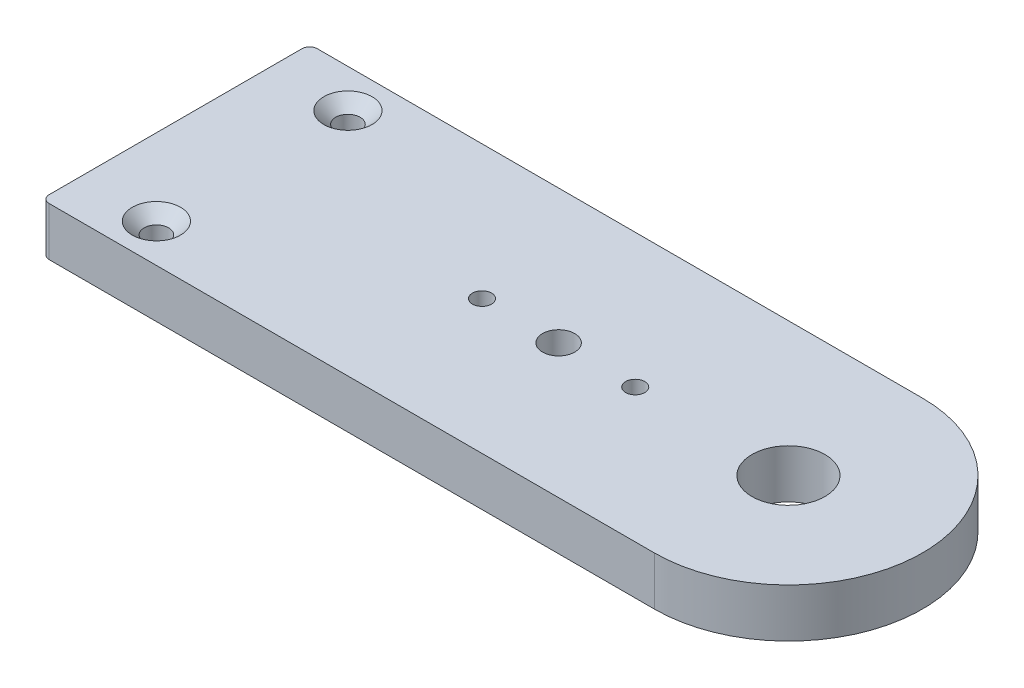
SolidWorks part; units mm, degrees
other "Markup1"
sketch "Sketch6" plane through (50.3553, 0, 50.3553) normal (0.291, 0.9567, 0.0091) x (0.9567, -0.291, -0.0015)
material "5052-H32"
ref_plane "Front Plane" through (0, 0, 0) normal (0, 0, 1) x (1, 0, 0)
ref_plane "Top Plane" through (0, 0, 0) normal (0, 1, 0) x (1, 0, 0)
ref_plane "Right Plane" through (0, 0, 0) normal (1, 0, 0) x (0, 0, -1)
sketch "Sketch2" plane through (0, 0, 0) normal (0, 1, 0) x (1, 0, 0)
  line L0 (0, 0) -> (70, 0) construction
  line L5 (0, 12.5) -> (0, -12.5) construction
  line L6 (-10, 17.5) -> (-10, -17.5)
  line L7 (-10, 17.5) -> (70, 17.5)
  line L8 (-10, -17.5) -> (70, -17.5)
  line L10 (25, 5) -> (55, 5) construction
  line L11 (25, 5) -> (25, -5) construction
  line L12 (25, -5) -> (55, -5) construction
  line L13 (55, 5) -> (55, -5) construction
  circle A0 centre (70, 0) radius 4.7625
  arc A2 (70, 17.5) -> (70, -17.5) centre (70, 0) cw
  circle A3 centre (0, 12.5) radius 1.5 construction
  circle A8 centre (70, 0) radius 37 construction
  circle A10 centre (0, -12.5) radius 1.5 construction
  circle A11 centre (30, 0) radius 1.5 construction
  circle A12 centre (50, 0) radius 1.5 construction
  circle A13 centre (40, 0) radius 2.5 construction
  point P0 (0, 0)
  point P21 (25, 0)
  point P27 (40, 5)
  point P28 (40, 0)
  dimension "D4" = 9.525
  dimension "D5" = 17.5
  dimension "D6" = 20
  dimension "D7" = 3
  dimension "D8" = 30
  dimension "D9" = 74
  dimension "D11" = 5
  dimension "D13" = 5
  dimension "D1" = 25
  dimension "D2" = 10
  dimension "D3" = 70
  dimension "D10" = 30
  dimension "D12" = 10
extrude "Boss-Extrude1" add sketch "Sketch2" against normal blind 6.35 contours L8 A2 L7
hole_wizard "CSK for M3 Flat Head Machine Screw1" positions "3DSketch1" profile "Sketch3" countersink size "M3" standard "ANSI Metric" end condition up to next
sketch3d "3DSketch1"
  point P0 (0, 0, -12.5)
  point P13 (0, 0, 12.5)
sketch "Sketch3" plane through (0, 0, -12.5) normal (1, 0, 0) x (0, 0, 1)
  line L0 (0, 0) -> (0, 6.35)
  line L1 (0, 6.35) -> (1.6, 6.35)
  line L2 (1.6, 6.35) -> (1.6, 1.55)
  line L3 (1.6, 1.55) -> (3.15, 0)
  line L5 (3.15, 0) -> (0, 0)
  line L6 (-1.6, 1.55) -> (-3.15, 0) construction
  line L11 (0, -6.35) -> (0, 107.95) construction
  dimension "Thru Hole Dia." = 3.2
  dimension "Thru Hole Depth" = 6.35
  dimension "Near C'Sink Dia." = 6.3
  dimension "Near C'Sink Angle" = 90
hole_wizard "Tap Drill for M3x0.5 Tap1" positions "3DSketch2" profile "Sketch7" hole size "M3x0.5" standard "ANSI Metric" end condition up to next
sketch3d "3DSketch2"
  point P0 (30, 0, 0)
  point P2 (50, 0, 0)
sketch "Sketch7" plane through (30, 0, 0) normal (1, 0, 0) x (0, 0, 1)
  line L0 (0, 0) -> (0, 6.35)
  line L1 (0, 6.35) -> (1.25, 6.35)
  line L2 (1.25, 6.35) -> (1.25, 0)
  line L5 (1.25, 0) -> (0, 0)
  line L11 (0, -6.35) -> (0, 107.95) construction
  dimension "Thru Hole Dia." = 2.5
  dimension "Thru Hole Depth" = 6.35
fillet "Fillet1" radius 1 2 edges at (-10, -3.175, -17.5) (-10, -3.175, 17.5)
hole_wizard "Tap Drill for M5x0.8 Tap1" positions "3DSketch4" profile "Sketch9" hole size "M5x0.8" standard "ANSI Metric" end condition up to next
sketch3d "3DSketch4"
  point P0 (40, 0, 0)
  point P3 (40, 0, 0)
sketch "Sketch9" plane through (40, 0, 0) normal (1, 0, 0) x (0, 0, 1)
  line L0 (0, 0) -> (0, 6.35)
  line L1 (0, 6.35) -> (2.1, 6.35)
  line L2 (2.1, 6.35) -> (2.1, 0)
  line L5 (2.1, 0) -> (0, 0)
  line L11 (0, -6.35) -> (0, 107.95) construction
  dimension "Thru Hole Dia." = 4.2
  dimension "Thru Hole Depth" = 6.35
